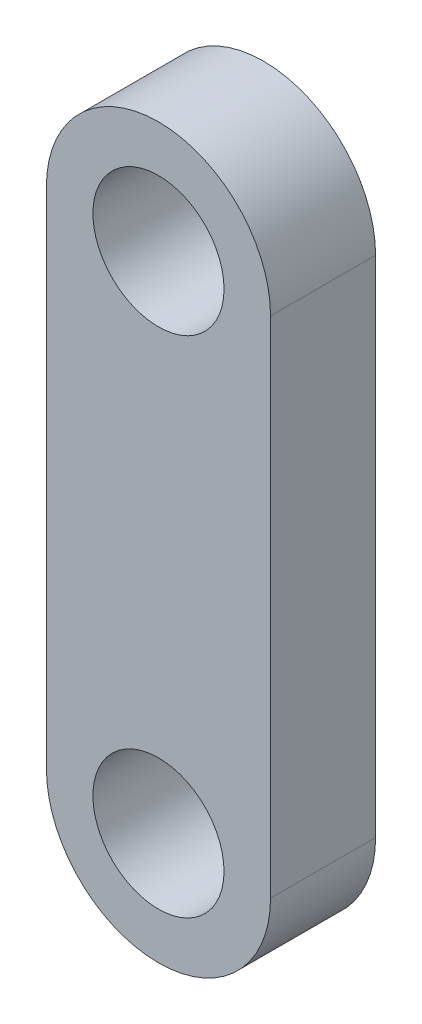
SolidWorks part; units mm, degrees
material "Titanium"
ref_plane "Front Plane" through (0, 0, 0) normal (0, 0, 1) x (1, 0, 0)
ref_plane "Top Plane" through (0, 0, 0) normal (0, 1, 0) x (1, 0, 0)
ref_plane "Right Plane" through (0, 0, 0) normal (1, 0, 0) x (0, 0, -1)
sketch "Sketch1" plane through (0, 0, 0) normal (0, 0, 1) x (1, 0, 0)
  line L3 (-3.2, 14.4) -> (-3.2, 0)
  line L4 (1.65, 0) -> (-1.65, 0) construction
  line L5 (3.2, 14.4) -> (3.2, 0)
  circle A2 centre (0, 0) radius 1.872
  circle A3 centre (0, 14.4) radius 1.872
  arc A4 (3.2, 14.4) -> (-3.2, 14.4) centre (0, 14.4) ccw
  arc A5 (-3.2, 0) -> (3.2, 0) centre (0, 0) ccw
  dimension "D1" = 6.4
  dimension "D2" = 3.744
  dimension "D3" = 14.4
extrude "Boss-Extrude1" add sketch "Sketch1" along normal blind 3
equation "\"bScale\"= 8"
equation "\"lScale\"= 8"
equation "\"D1@Sketch1\"=.8*\"bScale\""
equation "\"D2@Sketch1\"=0.468 * \"bScale\""
equation "\"D3@Sketch1\"=1.8*\"lScale\""
